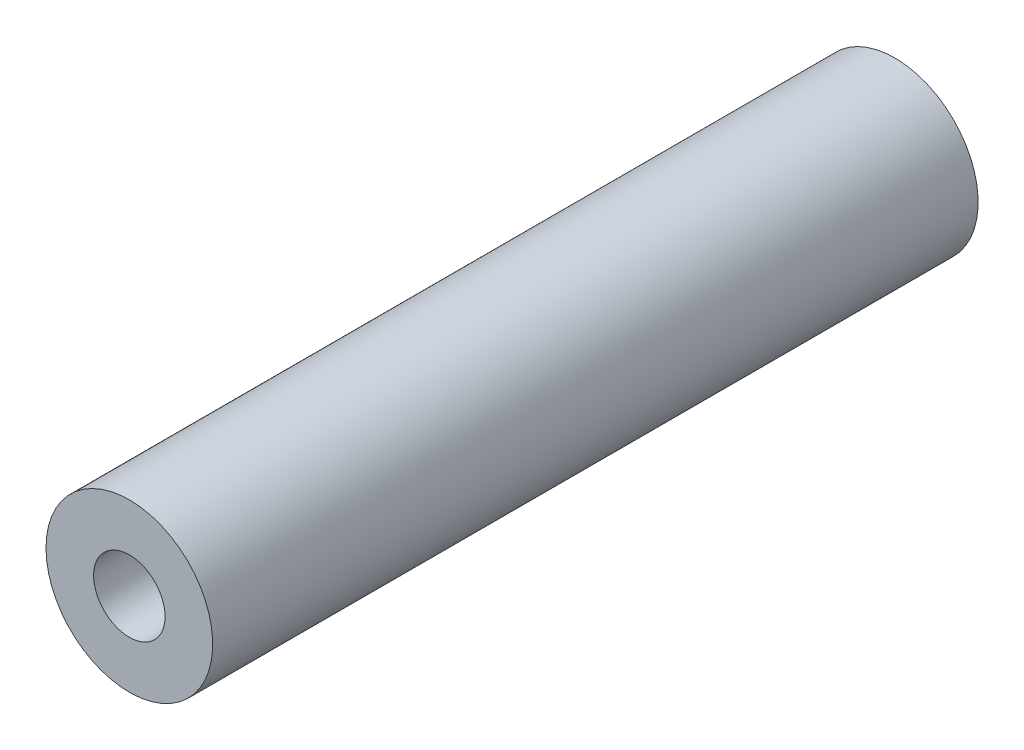
SolidWorks part; units mm, degrees
material "Liga 1060"
ref_plane "Plano frontal" through (0, 0, 0) normal (0, 0, 1) x (1, 0, 0)
ref_plane "Plano superior" through (0, 0, 0) normal (0, 1, 0) x (1, 0, 0)
ref_plane "Plano direito" through (0, 0, 0) normal (1, 0, 0) x (0, 0, -1)
sketch "Esboço1" plane through (0, 0, 0) normal (0, 0, 1) x (1, 0, 0)
  circle A0 centre (0, 0) radius 4.9
  dimension "D1" = 9.8
extrude "Ressalto-extrusão1" add sketch "Esboço1" along normal blind 45
hole_wizard "Furo roscado de M51" positions "3DSketch1" profile "Esboço2" tap size "M5" standard "ISO"
sketch3d "3DSketch1"
  line L0 (0, 0, 45) -> (0, 0, 0) construction
  point P0 (0, 0, 0)
  point P5 (0, 0, 45)
sketch "Esboço2" plane through (0, 0, 45) normal (1, 0, 0) x (0, -1, 0)
  line L0 (0, 0) -> (0, 15.2618)
  line L1 (0, 15.2618) -> (2.1, 14)
  line L2 (2.1, 14) -> (2.1, 0)
  line L5 (2.1, 0) -> (0, 0)
  line L10 (0, 15.2618) -> (-2.1, 14) construction
  line L11 (0, -6.35) -> (0, 107.95) construction
  dimension "Tap Drill Dia." = 4.2
  dimension "Tap Drill Depth" = 14
  dimension "Drill Angle" = 118
cosmetic thread "Rosca de furo2" parameters "D1"=10, "D2"=5
sketch "Esboço3" plane through (0, 0, 0) normal (0, 0, -1) x (-1, 0, 0)
  line L0 (-3, 0) -> (3, 0) construction
  circle A0 centre (0, 0) radius 3 construction
  point P3 (0, 3)
  dimension "D1" = 6
hole_wizard "Furo roscado de M21" positions "3DSketch2" profile "Esboço6" tap size "M2" standard "ISO"
sketch3d "3DSketch2"
  point P0 (0, 3, 0)
sketch "Esboço6" plane through (0, 3, 0) normal (1, 0, 0) x (0, 1, 0)
  line L0 (0, 0) -> (0, 8.4807)
  line L1 (0, 8.4807) -> (0.8, 8)
  line L2 (0.8, 8) -> (0.8, 0)
  line L5 (0.8, 0) -> (0, 0)
  line L10 (0, 8.4807) -> (-0.8, 8) construction
  line L11 (0, -6.35) -> (0, 107.95) construction
  dimension "Tap Drill Dia." = 1.6
  dimension "Tap Drill Depth" = 8
  dimension "Drill Angle" = 118
cosmetic thread "Rosca de furo3" parameters "D1"=4, "D2"=2
pattern_circular "PadrãoCircular1" count 3 over 360 about axis through (0, 0, 0) along (0, 0, 1) of "Furo roscado de M21"
cosmetic thread "Rosca de furo4" parameters "D1"=4, "D2"=2
cosmetic thread "Rosca de furo5" parameters "D1"=4, "D2"=2
